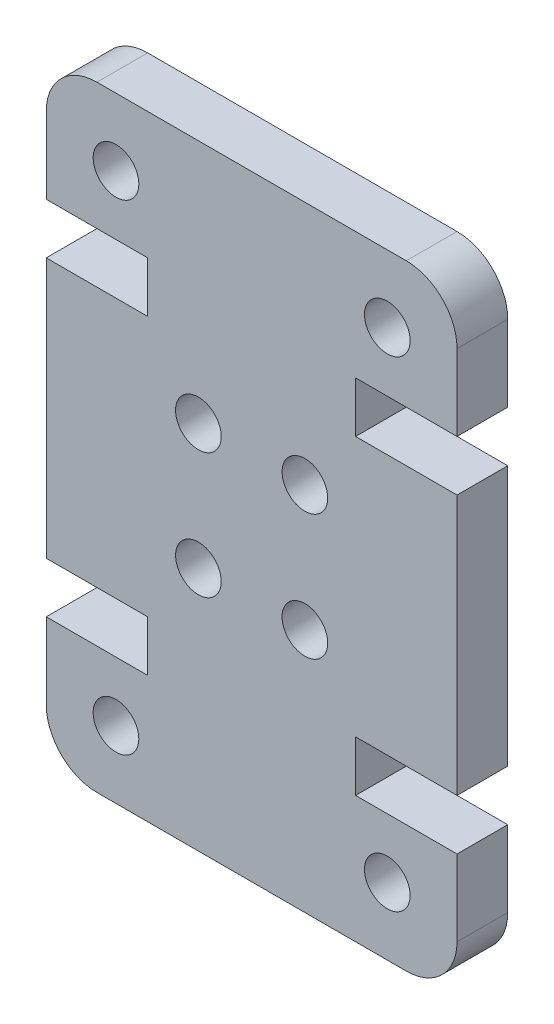
SolidWorks part; units mm, degrees
ref_plane "Front Plane" through (0, 0, 0) normal (0, 0, 1) x (1, 0, 0)
ref_plane "Top Plane" through (0, 0, 0) normal (0, 1, 0) x (1, 0, 0)
ref_plane "Right Plane" through (0, 0, 0) normal (1, 0, 0) x (0, 0, -1)
sketch "Sketch1" plane through (0, 0, 0) normal (0, 0, 1) x (1, 0, 0)
  line L0 (8.1, 24.26) -> (8.1, 0) construction
  line L1 (0, 12.13) -> (16.2, 12.13) construction
  line L2 (16.2, 17.26) -> (16.2, 7)
  line L3 (16.2, 2) -> (16.2, 5)
  line L4 (12.2, 5) -> (16.2, 5)
  line L5 (16.2, 7) -> (12.2, 7)
  line L6 (12.2, 7) -> (12.2, 5)
  line L7 (0, 22.26) -> (0, 19.26)
  line L8 (4, 19.26) -> (0, 19.26)
  line L9 (0, 17.26) -> (4, 17.26)
  line L10 (4, 17.26) -> (4, 19.26)
  line L11 (2, 24.26) -> (14.2, 24.26)
  line L12 (12.2, 17.26) -> (12.2, 19.26)
  line L13 (16.2, 17.26) -> (12.2, 17.26)
  line L14 (12.2, 19.26) -> (16.2, 19.26)
  line L15 (16.2, 22.26) -> (16.2, 19.26)
  line L21 (2, 0) -> (14.2, 0)
  line L25 (4, 7) -> (4, 5)
  line L28 (0, 7) -> (4, 7)
  line L30 (4, 5) -> (0, 5)
  line L34 (0, 2) -> (0, 5)
  line L38 (0, 17.26) -> (0, 7)
  circle A0 centre (13.45, 2.6536) radius 0.9
  circle A1 centre (10.2, 9.6536) radius 0.9
  arc A2 (16.2, 2) -> (14.2, 0) centre (14.2, 2) cw
  circle A3 centre (2.75, 21.6064) radius 0.9
  circle A4 centre (6, 14.6064) radius 0.9
  arc A5 (0, 22.26) -> (2, 24.26) centre (2, 22.26) cw
  arc A6 (16.2, 22.26) -> (14.2, 24.26) centre (14.2, 22.26) ccw
  circle A7 centre (10.2, 14.6064) radius 0.9
  circle A8 centre (13.45, 21.6064) radius 0.9
  arc A17 (0, 2) -> (2, 0) centre (2, 2) ccw
  circle A19 centre (6, 9.6536) radius 0.9
  circle A21 centre (2.75, 2.6536) radius 0.9
  point P16 (8.1, 12.13)
  dimension "D1" = 1.8
  dimension "D2" = 2
  dimension "D3" = 2.75
  dimension "D4" = 6
  dimension "D5" = 8.1
  dimension "D6" = 2.6536
  dimension "D9" = 9.6536
  dimension "D10" = 12.13
  dimension "D7" = 5
extrude "Boss-Extrude1" add sketch "Sketch1" along normal blind 2
equation "\"D5@Sketch1\"= \"fingerWidth@parametersSketch@prostheticParameters.SLDPRT\" / 2'PIP width"
equation "\"D10@Sketch1\"= ( \"HL@parametersSketch@prostheticParameters.SLDPRT\" * 0.196 - 4 - 8 ) / 2 'PIP length - Sil. Sht DIP - Sil. Sht PIP"
equation "\"D1@Sketch1\"= 1.5 + \"tol1@parametersSketch@prostheticParameters.SLDPRT\""
